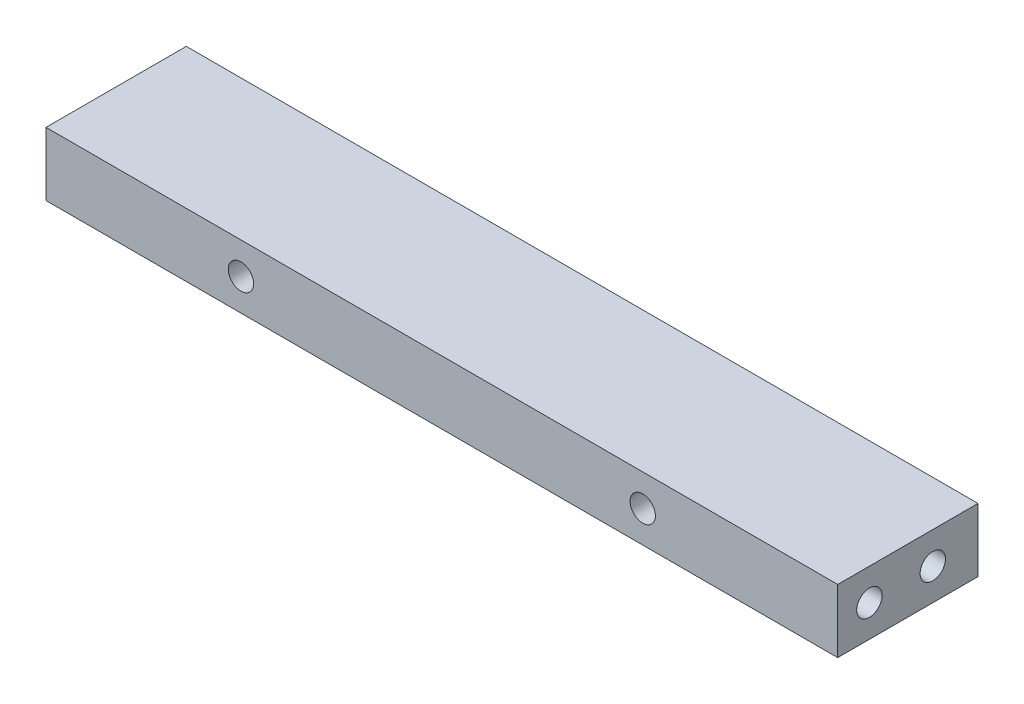
SolidWorks part; units mm, degrees
material "6061-T6 (SS)"
ref_plane "前视基准面" through (0, 0, 0) normal (0, 0, 1) x (1, 0, 0)
ref_plane "上视基准面" through (0, 0, 0) normal (0, 1, 0) x (1, 0, 0)
ref_plane "右视基准面" through (0, 0, 0) normal (1, 0, 0) x (0, 0, -1)
other "Configuration Table"
sketch "草图1" plane through (0, 0, 0) normal (0, 0, 1) x (1, 0, 0)
  line L1 (-0.3, -4.3) -> (49.65, -4.3)
  line L2 (-0.3, -4.3) -> (-0.3, -0.3)
  line L3 (-0.3, -0.3) -> (49.65, -0.3)
  line L4 (49.65, -4.3) -> (49.65, -0.3)
  dimension "D1" = 49.65
  dimension "D2" = 0.3
  dimension "D3" = 0.3
  dimension "D4" = 4.3
extrude "Main_Stock" add sketch "草图1" along normal blind 8.8519 from offset 2.2481
sketch "草图2" plane through (0, 0, 11.1) normal (0, 0, 1) x (1, 0, 0)
  circle A0 centre (12, -2.3) radius 0.8
  circle A1 centre (37.35, -2.3) radius 0.8
  dimension "D1" = 1.6
  dimension "D2" = 12
  dimension "D3" = 37.35
  dimension "D4" = 2.3
extrude "Frame_2xD1p6_Through" cut sketch "草图2" against normal through all
cosmetic thread "Frame_M2_Through_Cosmetic_1" parameters "D2"=2
cosmetic thread "Frame_M2_Through_Cosmetic_2" parameters "D2"=2
sketch "草图3" plane through (-0.3, 0, 0) normal (-1, 0, 0) x (0, 0, 1)
  circle A0 centre (5.1, -2.3) radius 0.8
  circle A1 centre (9.1, -2.3) radius 0.8
  dimension "D1" = 1.6
  dimension "D2" = 5.1
  dimension "D3" = 9.1
  dimension "D4" = 2.3
extrude "Corner_L_2xD1p6_Blind5" cut sketch "草图3" against normal blind 5
cosmetic thread "Corner_L_M2_Cosmetic_1" parameters "D1"=4.5, "D2"=2
cosmetic thread "Corner_L_M2_Cosmetic_2" parameters "D1"=4.5, "D2"=2
sketch "草图4" plane through (49.65, 0, 0) normal (1, 0, 0) x (0, 0, -1)
  circle A0 centre (-5.1, -2.3) radius 0.8
  circle A1 centre (-9.1, -2.3) radius 0.8
  dimension "D1" = 1.6
  dimension "D2" = 5.1
  dimension "D3" = 9.1
  dimension "D4" = 2.3
extrude "Corner_R_2xD1p6_Blind5" cut sketch "草图4" against normal blind 5
cosmetic thread "Corner_R_M2_Cosmetic_1" parameters "D1"=4.5, "D2"=2
cosmetic thread "Corner_R_M2_Cosmetic_2" parameters "D1"=4.5, "D2"=2
